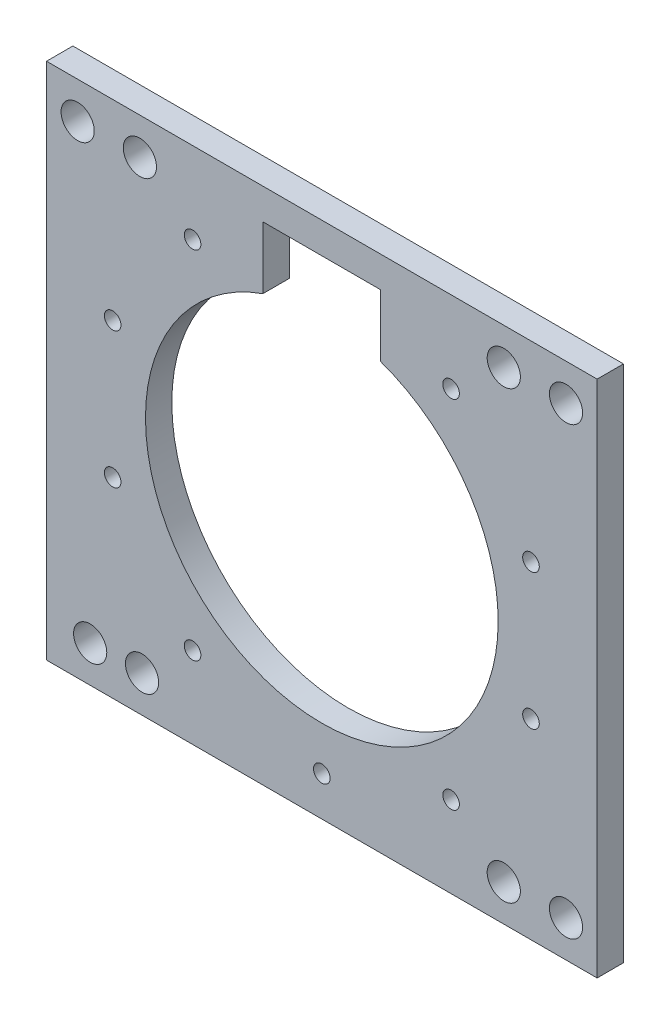
SolidWorks part; units mm, degrees
material "6061 Alloy"
ref_plane "Front Plane" through (0, 0, 0) normal (0, 0, 1) x (1, 0, 0)
ref_plane "Top Plane" through (0, 0, 0) normal (0, 1, 0) x (1, 0, 0)
ref_plane "Right Plane" through (0, 0, 0) normal (1, 0, 0) x (0, 0, -1)
sketch "Sketch1" plane through (0, 0, 0) normal (0, 0, 1) x (1, 0, 0)
  line L7 (-14.2757, 39.7547) -> (-14.2757, 54.7547)
  line L8 (-14.2757, 54.7547) -> (14.1243, 54.7547)
  line L9 (14.1243, 54.7547) -> (14.1243, 39.7547)
  circle A1 centre (-50.4817, 16.0751) radius 2
  circle A2 centre (-50.4817, -16.6807) radius 2
  circle A3 centre (-31.2283, -43.1807) radius 2
  circle A4 centre (-0.0757, -53.3028) radius 2
  circle A5 centre (31.0769, -43.1807) radius 2
  circle A6 centre (50.3303, -16.6807) radius 2
  circle A7 centre (50.3303, 16.0751) radius 2
  circle A8 centre (31.0769, 42.5751) radius 2
  circle A10 centre (-31.2283, 42.5751) radius 2
  arc A11 (-14.2757, 39.7547) -> (14.1243, 39.7547) centre (-0.0757, -0.3028) ccw
sketch "Sketch2" plane through (0, 0, 0) normal (0, 0, 1) x (1, 0, 0)
  line L0 (-66.4257, -62.8028) -> (-66.4257, 62.1972)
  line L1 (-66.4257, 62.1972) -> (66.2743, 62.1972)
  line L3 (-66.4257, -62.8028) -> (66.2743, -62.8028)
  line L4 (66.2743, -62.8028) -> (66.2743, 62.1972)
extrude "Boss-Extrude1" add sketch "Sketch2" along normal blind 6.35
extrude "Cut-Extrude1" cut sketch "Sketch1" along normal up to surface (6.35 mm away) up to face at (-0.0757, -0.3028, 6.35)
sketch "Sketch6" plane through (0, 0, 6.35) normal (0, 0, 1) x (1, 0, 0)
  circle A8 centre (58.7743, -53.9903) radius 4
  circle A9 centre (43.7743, -53.9903) radius 4
  circle A10 centre (-55.9033, -53.9903) radius 4
  circle A11 centre (-43.4033, -53.9903) radius 4
  circle A12 centre (-58.9257, 53.3847) radius 4
  circle A13 centre (-43.9257, 53.3847) radius 4
  circle A14 centre (43.7743, 53.3847) radius 4
  circle A15 centre (58.7743, 53.3847) radius 4
extrude "Cut-Extrude3" cut sketch "Sketch6" against normal up to surface (6.35 mm away) up to face at (-48.4817, -16.6807, 0)
sketch "Sketch7" plane through (0, 0, 6.35) normal (0, 0, 1) x (1, 0, 0)
  line L14 (14.1243, 54.7547) -> (14.1243, 39.7547) construction
  line L15 (-14.2757, 39.7547) -> (-14.2757, 54.7547) construction
  line L16 (-14.2757, 54.7547) -> (14.1243, 54.7547) construction
  line L17 (14.1243, 54.7547) -> (14.1243, 39.7547)
  line L26 (-14.2757, 39.7547) -> (-14.2757, 54.7547)
  line L27 (-14.2757, 54.7547) -> (14.1243, 54.7547)
  line L28 (-0.0757, 54.7547) -> (-0.0757, 62.1972)
  line L29 (66.2743, 62.1972) -> (-66.4257, 62.1972) construction
  arc A36 (-14.2757, 39.7547) -> (14.1243, 39.7547) centre (-0.0757, -0.3028) ccw construction
  arc A37 (-14.2757, 39.7547) -> (14.1243, 39.7547) centre (-0.0757, -0.3028) ccw
